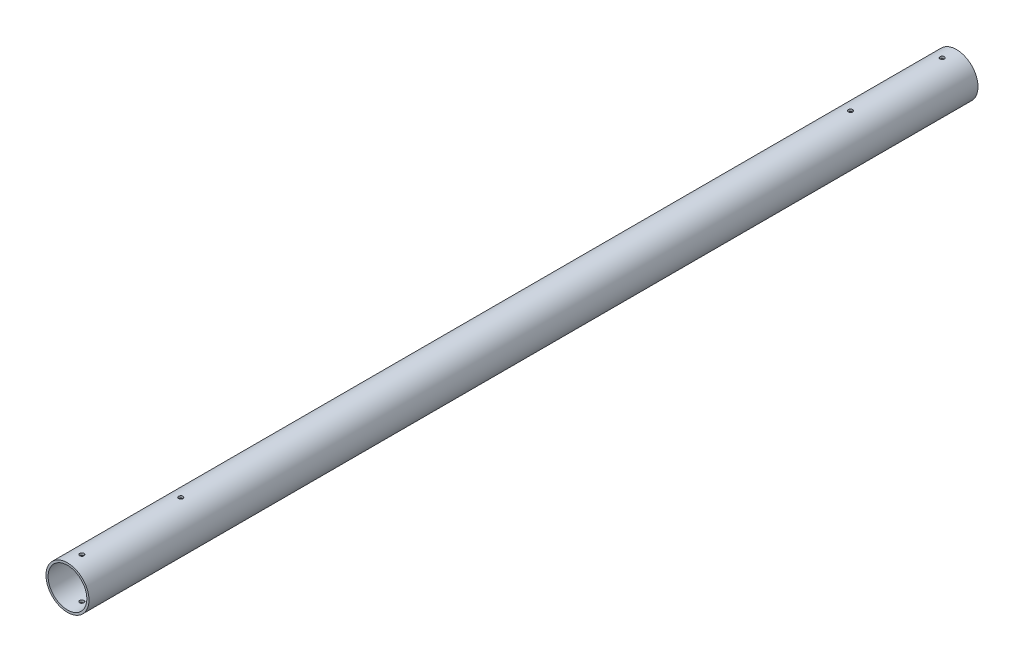
SolidWorks part; units mm, degrees
ref_plane "Front Plane" through (0, 0, 0) normal (0, 0, 1) x (1, 0, 0)
ref_plane "Top Plane" through (0, 0, 0) normal (0, 1, 0) x (1, 0, 0)
ref_plane "Right Plane" through (0, 0, 0) normal (1, 0, 0) x (0, 0, -1)
sketch "Sketch1" plane through (0, 0, 0) normal (0, 0, 1) x (1, 0, 0)
  circle A0 centre (0, 0) radius 15
  dimension "D1" = 30
extrude "Boss-Extrude1" add sketch "Sketch1" along normal blind 620
sketch "Sketch2" plane through (0, 0, 0) normal (0, 0, -1) x (-1, 0, 0)
  circle A0 centre (0, 0) radius 13.5
  dimension "D1" = 27
extrude "Cut-Extrude1" cut sketch "Sketch2" against normal through all
sketch "Sketch3" plane through (0, 0, 0) normal (0, 1, 0) x (1, 0, 0)
  line L0 (-15, -310) -> (25.6457, -310) construction
  line L1 (-15, 0) -> (-15, -620) construction
  line L2 (13.5, 0) -> (-13.5, 0) construction
  line L3 (-15, -620) -> (15, -620) construction
  circle A0 centre (0, -10) radius 1.5
  circle A1 centre (0, -610) radius 1.5
  circle A2 centre (0, -74) radius 1.5
  circle A3 centre (0, -541) radius 1.5
  dimension "D1" = 10
  dimension "D2" = 3
  dimension "D5" = 3
  dimension "D6" = 3
  dimension "D3" = 74
  dimension "D4" = 79
extrude "Cut-Extrude2" cut sketch "Sketch3" against normal through all both and the other way through all
